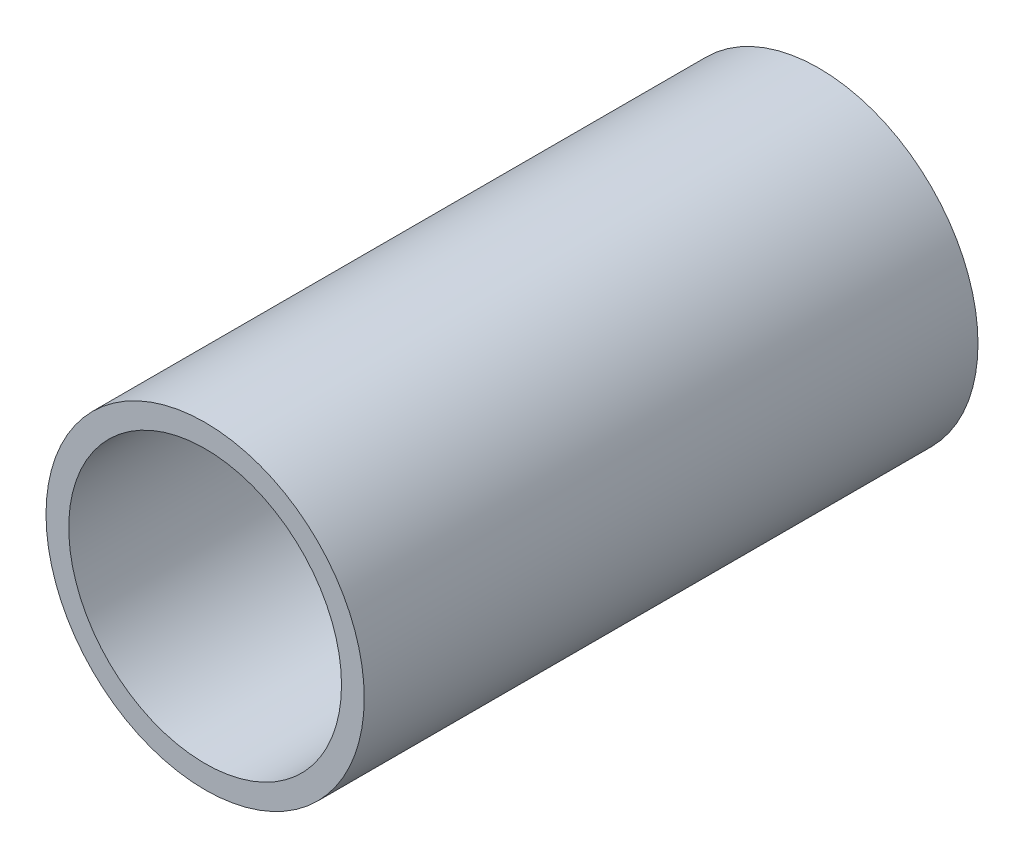
SolidWorks part; units mm, degrees
material "Acrylic (Medium-high impact)"
ref_plane "Front Plane" through (0, 0, 0) normal (0, 0, 1) x (1, 0, 0)
ref_plane "Top Plane" through (0, 0, 0) normal (0, 1, 0) x (1, 0, 0)
ref_plane "Right Plane" through (0, 0, 0) normal (1, 0, 0) x (0, 0, -1)
sketch "Sketch1" plane through (0, 0, 0) normal (0, 0, 1) x (1, 0, 0)
  circle A0 centre (0, 0) radius 19.05
  circle A1 centre (0, 0) radius 22.225
  dimension "D1" = 38.1
  dimension "D2" = 44.45
extrude "Boss-Extrude1" add sketch "Sketch1" along normal blind 85.725
